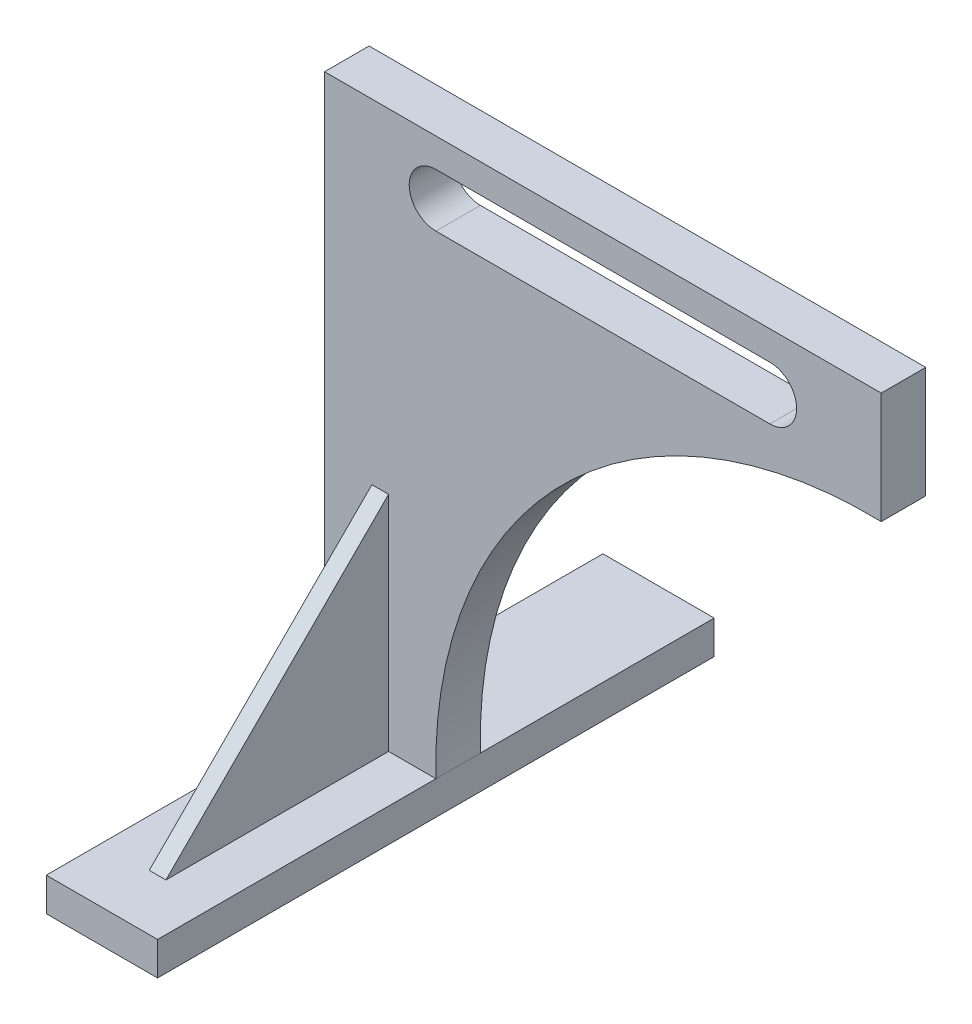
SolidWorks part; units mm, degrees
ref_plane "Front Plane" through (0, 0, 0) normal (0, 0, 1) x (1, 0, 0)
ref_plane "Top Plane" through (0, 0, 0) normal (0, 1, 0) x (1, 0, 0)
ref_plane "Right Plane" through (0, 0, 0) normal (1, 0, 0) x (0, 0, -1)
sketch "Sketch1" plane through (0, 0, 0) normal (0, 0, 1) x (1, 0, 0)
  line L1 (-25, 7.5) -> (25, 7.5)
  line L2 (-25, 7.5) -> (-25, -7.5)
  line L3 (-25, -7.5) -> (25, -7.5)
  line L4 (25, 7.5) -> (25, -7.5)
  line L5 (-25, 7.5) -> (25, -7.5) construction
  line L6 (-25, -7.5) -> (25, 7.5) construction
  point P0 (0, 0)
  dimension "D1" = 50
  dimension "D2" = 15
extrude "Boss-Extrude1" add sketch "Sketch1" against normal blind 250
sketch "Sketch2" plane through (0, 0, 0) normal (0, 0, 1) x (1, 0, 0)
  line L0 (-25, 7.5) -> (-25, 257.5)
  line L1 (-25, 257.5) -> (225, 257.5)
  line L3 (25, 7.5) -> (-25, 7.5) construction
  line L4 (25, 7.5) -> (-25, 7.5)
  line L5 (225, 257.5) -> (225, 207.5)
  arc A0 (225, 207.5) -> (25, 7.5) centre (219.9342, 12.5658) ccw
  dimension "D3" = 195
  dimension "D1" = 250
  dimension "D2" = 250
  dimension "D4" = 50
extrude "Boss-Extrude3" add sketch "Sketch2" against normal mid plane 20 from offset 135 offset against normal yes
sketch "Sketch4" plane through (0, 0, 0) normal (1, 0, 0) x (0, 0, -1)
  line L0 (25, 7.5) -> (125, 107.5)
  line L1 (125, 7.5) -> (0, 7.5) construction
  line L2 (125, 207.5658) -> (125, 7.5) construction
  line L3 (125, 107.5) -> (125, 7.5)
  line L4 (125, 7.5) -> (25, 7.5)
  dimension "D1" = 100
  dimension "D2" = 100
extrude "Boss-Extrude4" add sketch "Sketch4" along normal mid plane 7.5
sketch "Sketch5" plane through (0, 0, -125) normal (0, 0, 1) x (1, 0, 0)
  line L0 (25, 232.5) -> (175, 232.5) construction
  line L1 (25, 244.5) -> (175, 244.5)
  line L2 (25, 220.5) -> (175, 220.5)
  line L3 (225, 257.5) -> (-25, 257.5) construction
  line L4 (-25, 257.5) -> (-25, 7.5) construction
  arc A0 (25, 244.5) -> (25, 220.5) centre (25, 232.5) ccw
  arc A1 (175, 220.5) -> (175, 244.5) centre (175, 232.5) ccw
  point P2 (100, 232.5)
  point P9 (29.9999, 230.7144)
  dimension "D3" = 12
  dimension "D1" = 150
  dimension "D2" = 25
  dimension "D4" = 50
extrude "Cut-Extrude1" cut sketch "Sketch5" against normal through all
